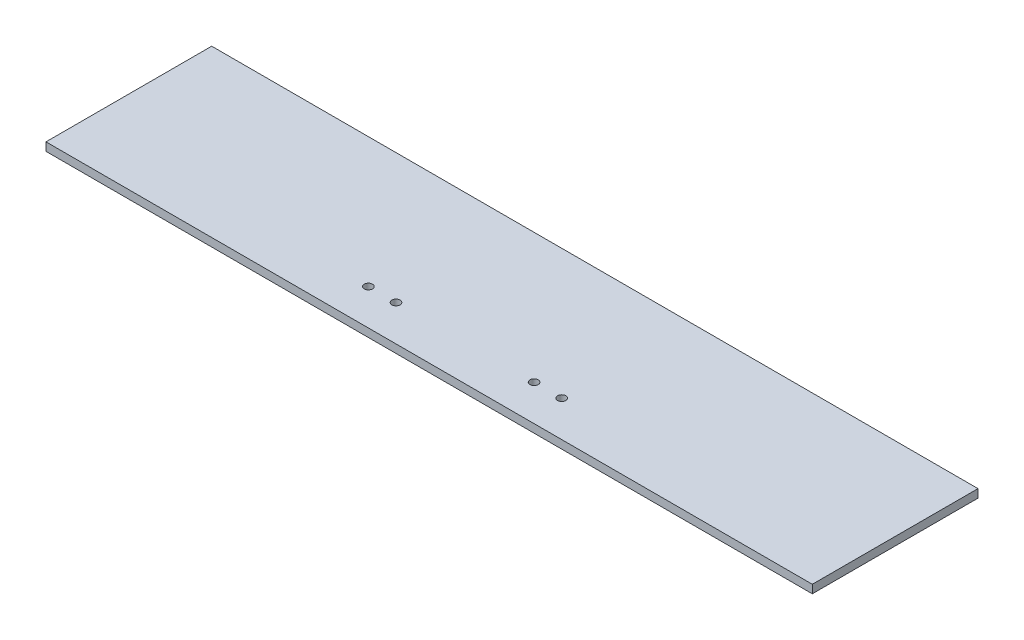
SolidWorks part; units mm, degrees
ref_plane "Front Plane" through (0, 0, 0) normal (0, 0, 1) x (1, 0, 0)
ref_plane "Top Plane" through (0, 0, 0) normal (0, 1, 0) x (1, 0, 0)
ref_plane "Right Plane" through (0, 0, 0) normal (1, 0, 0) x (0, 0, -1)
sketch "Sketch1" plane through (0, 0, 0) normal (0, 1, 0) x (1, 0, 0)
  line L1 (-138.75, 30) -> (138.75, 30)
  line L2 (-138.75, 30) -> (-138.75, -30)
  line L3 (-138.75, -30) -> (138.75, -30)
  line L4 (138.75, 30) -> (138.75, -30)
  line L5 (-138.75, 30) -> (138.75, -30) construction
  line L6 (-138.75, -30) -> (138.75, 30) construction
  point P0 (0, 0)
extrude "Boss-Extrude1" add sketch "Sketch1" along normal blind 3
sketch "Sketch3" plane through (0, 3, 0) normal (0, 1, 0) x (1, 0, 0)
  line L0 (0, -30) -> (25, -30) construction
  line L1 (-138.75, -30) -> (138.75, -30) construction
  line L2 (25, -30) -> (25, -17) construction
  line L3 (25, -17) -> (35, -17) construction
  line L4 (0, -30) -> (0, -13.6167) construction
  circle A0 centre (25, -17) radius 1.5
  circle A1 centre (35, -17) radius 1.5
  circle A2 centre (-35, -17) radius 1.5
  circle A3 centre (-25, -17) radius 1.5
extrude "Cut-Extrude1" cut sketch "Sketch3" against normal through all both
